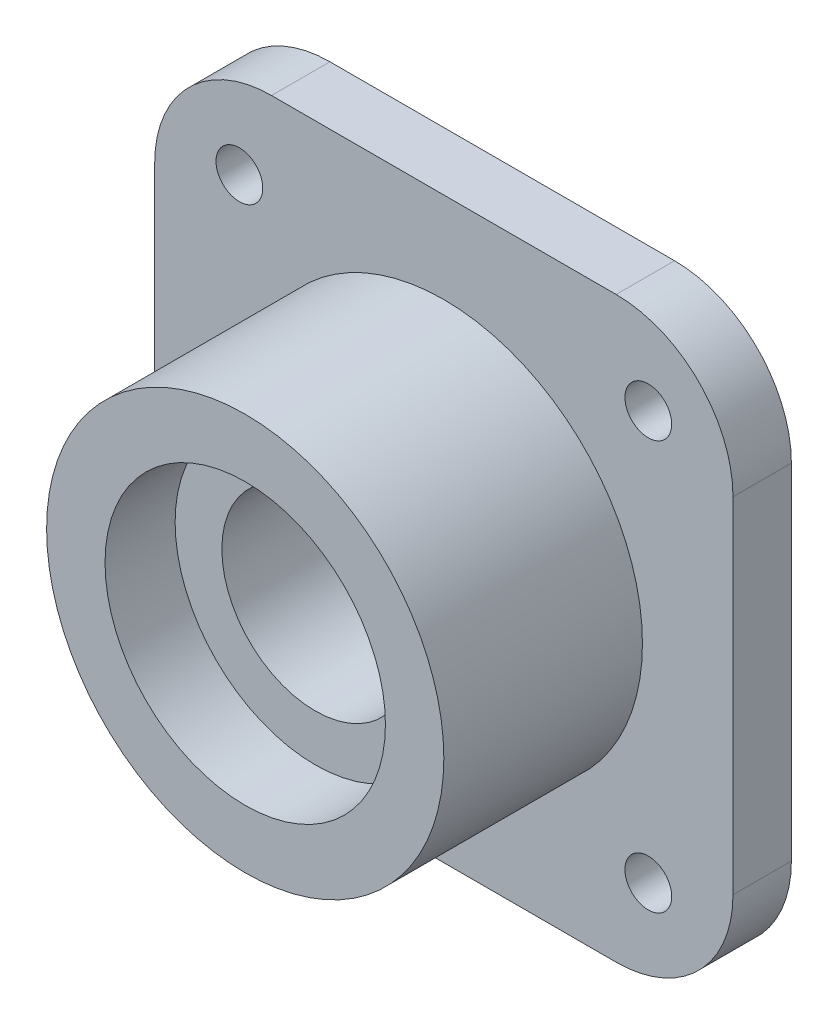
SolidWorks part; units mm, degrees
material "6061-T6 (SS)"
ref_plane "Front Plane" through (0, 0, 0) normal (0, 0, 1) x (1, 0, 0)
ref_plane "Top Plane" through (0, 0, 0) normal (0, 1, 0) x (1, 0, 0)
ref_plane "Right Plane" through (0, 0, 0) normal (1, 0, 0) x (0, 0, -1)
sketch "Sketch3" plane through (0, 0, 0) normal (1, 0, 0) x (0, 0, -1)
  line L0 (0, 0) -> (64.3605, 0) construction
  line L1 (0, 12) -> (6, 12)
  line L2 (6, 12) -> (6, 8)
  line L3 (6, 8) -> (16, 8)
  line L4 (16, 8) -> (16, 12)
  line L5 (16, 12) -> (22, 12)
  line L6 (22, 12) -> (22, 35)
  line L7 (22, 35) -> (17, 35)
  line L8 (17, 35) -> (17, 17)
  line L9 (17, 17) -> (0, 17)
  line L10 (0, 17) -> (0, 12)
  dimension "D1" = 12
  dimension "D2" = 8
  dimension "D3" = 5
  dimension "D4" = 10
  dimension "D5" = 6
  dimension "D6" = 5
  dimension "D7" = 35
revolve "Revolve1" add sketch "Sketch3" angle 360 about L0
sketch "Sketch4" plane through (0, 0, -17) normal (0, 0, 1) x (1, 0, 0)
  line L0 (-24.7487, 24.7487) -> (24.7487, 24.7487)
  line L1 (-24.7487, 24.7487) -> (-24.7487, -24.7487)
  line L2 (24.7487, 24.7487) -> (24.7487, -24.7487)
  line L3 (-24.7487, -24.7487) -> (24.7487, -24.7487)
  circle A0 centre (0, 0) radius 35 construction
  circle A1 centre (0, 0) radius 35
  point P6 (-24.7487, 0)
  point P8 (0, 24.7487)
  circle M6 centre (0, 0) radius 35
extrude "Cut-Extrude1" cut sketch "Sketch4" against normal blind 10 contours L2 M6 | L0 M6 | L1 M6 | L3 M6
fillet "Fillet1" radius 10 4 edges at (24.7487, 24.7487, -19.5) (24.7487, -24.7487, -19.5) (-24.7487, -24.7487, -19.5) (-24.7487, 24.7487, -19.5)
sketch "Sketch5" plane through (0, 0, -22) normal (0, 0, -1) x (-1, 0, 0)
  line L1 (-17.5, -17.5) -> (17.5, -17.5) construction
  line L2 (-17.5, -17.5) -> (-17.5, 17.5) construction
  line L3 (-17.5, 17.5) -> (17.5, 17.5) construction
  line L4 (17.5, -17.5) -> (17.5, 17.5) construction
  line L5 (-17.5, -17.5) -> (17.5, 17.5) construction
  line L6 (-17.5, 17.5) -> (17.5, -17.5) construction
  circle A0 centre (-17.5, 17.5) radius 2
  circle A1 centre (17.5, 17.5) radius 2
  circle A2 centre (17.5, -17.5) radius 2
  circle A3 centre (-17.5, -17.5) radius 2
  point P0 (0, 0)
  dimension "D2" = 4
  dimension "D1" = 35
extrude "Cut-Extrude2" cut sketch "Sketch5" against normal blind 10
